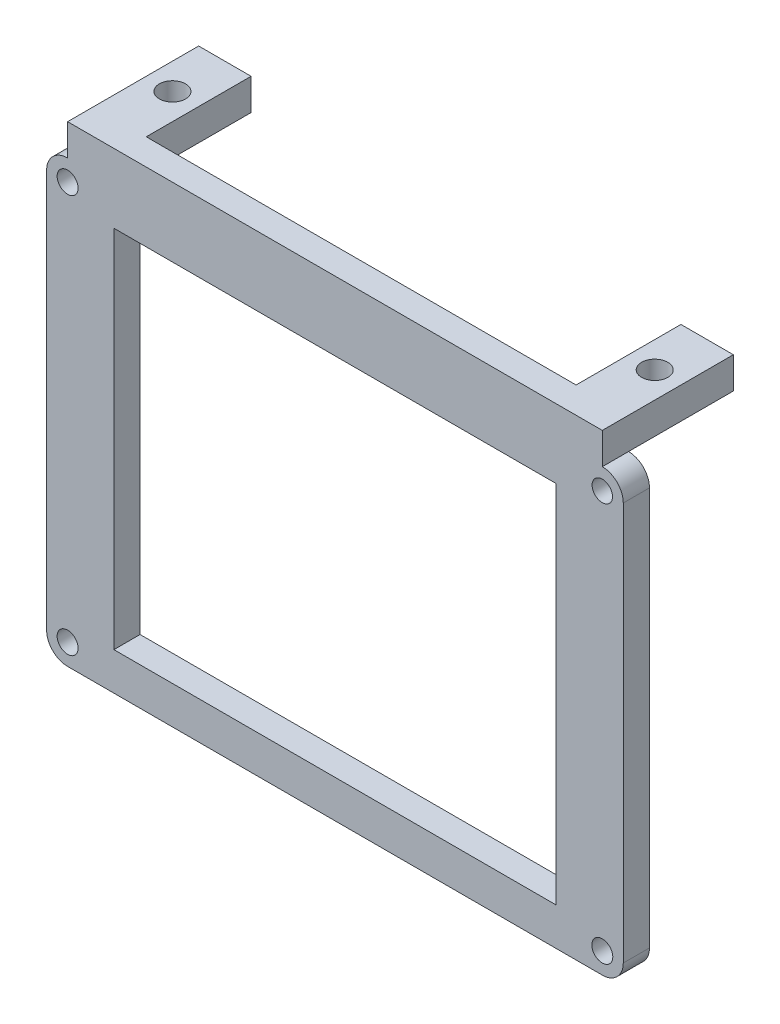
SolidWorks part; units mm, degrees
ref_plane "前视基准面" through (0, 0, 0) normal (0, 0, 1) x (1, 0, 0)
ref_plane "上视基准面" through (0, 0, 0) normal (0, 1, 0) x (1, 0, 0)
ref_plane "右视基准面" through (0, 0, 0) normal (1, 0, 0) x (0, 0, -1)
sketch "草图1" plane through (0, 0, 0) normal (0, 0, 1) x (1, 0, 0)
  line L0 (-38.0886, 27.2715) -> (71.9114, -56.7285) construction
  line L1 (-34.0886, 27.2715) -> (67.9114, 27.2715)
  line L2 (-38.0886, 23.2715) -> (-38.0886, -52.7285)
  line L3 (-34.0886, -56.7285) -> (67.9114, -56.7285)
  line L4 (71.9114, 23.2715) -> (71.9114, -52.7285)
  line L10 (-34.0886, 23.2715) -> (67.9114, -52.7285) construction
  line L11 (-34.0886, -52.7285) -> (67.9114, 23.2715) construction
  circle A0 centre (67.9114, 23.2715) radius 1.9459
  circle A1 centre (-34.0886, 23.2715) radius 2
  circle A2 centre (67.9114, -52.7285) radius 2
  circle A3 centre (-34.0886, -52.7285) radius 2
  arc A4 (67.9114, 27.2715) -> (71.9114, 23.2715) centre (67.9114, 23.2715) cw
  arc A5 (-34.0886, 27.2715) -> (-38.0886, 23.2715) centre (-34.0886, 23.2715) ccw
  arc A6 (-38.0886, -52.7285) -> (-34.0886, -56.7285) centre (-34.0886, -52.7285) ccw
  arc A7 (67.9114, -56.7285) -> (71.9114, -52.7285) centre (67.9114, -52.7285) ccw
  point P4 (16.9114, -14.7285)
  point P15 (71.9114, 27.2715)
  point P21 (-38.0886, -56.7285)
  dimension "D5" = 4
  dimension "D6" = 4
  dimension "D7" = 4
  dimension "D8" = 4
  dimension "D1" = 110
  dimension "D2" = 84
  dimension "D3" = 102
  dimension "D4" = 76
extrude "凸台-拉伸1" add sketch "草图1" along normal blind 5
sketch "草图2" plane through (0, 27.2715, 0) normal (0, 1, 0) x (1, 0, 0)
  line L0 (-34.0886, 0) -> (-24.0886, 20) construction
  line L1 (-34.0886, -5) -> (-24.0886, -5)
  line L2 (-34.0886, -5) -> (-34.0886, 20)
  line L3 (-34.0886, 20) -> (-24.0886, 20)
  line L4 (-24.0886, -5) -> (-24.0886, 20)
  line L5 (67.9114, -5) -> (57.9114, -5)
  line L6 (67.9114, -5) -> (67.9114, 20)
  line L7 (67.9114, 20) -> (57.9114, 20)
  line L8 (57.9114, -5) -> (57.9114, 20)
  line L9 (67.9114, 0) -> (57.9114, 20) construction
  line L10 (67.9114, 0) -> (-34.0886, 0) construction
  line L11 (-24.0886, -5) -> (57.9114, -5)
  line L12 (-24.0886, -5) -> (-24.0886, 0)
  line L13 (-24.0886, 0) -> (57.9114, 0)
  line L14 (57.9114, -5) -> (57.9114, 0)
  circle A0 centre (-29.0886, 10) radius 2.5
  circle A1 centre (62.9114, 10) radius 2.5
  line M10 (67.9114, 0) -> (-34.0886, 0)
  line M11 (-34.0886, 0) -> (-34.0886, -5)
  line M12 (-34.0886, -5) -> (67.9114, -5)
  line M13 (67.9114, -5) -> (67.9114, 0)
  dimension "D1" = 10
  dimension "D2" = 25
  dimension "D3" = 10
  dimension "D4" = 25
extrude "凸台-拉伸2" add sketch "草图2" along normal blind 6 contours L4 L3 L2 A0 M10 | L4 M12 M10 M11 | L8 L4 M12 M10 | L8 L6 L7 A1 M10 | L8 M12 M13 M10
sketch "草图3" plane through (0, 0, 5) normal (0, 0, 1) x (1, 0, 0)
  line L0 (-33.9461, 26.2295) -> (67.9114, -56.7285) construction
  line L1 (67.9114, -56.7285) -> (-34.0886, -56.7285) construction
  line L2 (-34.0886, -56.7285) -> (67.9114, 27.2715) construction
  line L4 (-25.2619, 20.0825) -> (59.0846, 20.0825)
  line L5 (-25.2619, 20.0825) -> (-25.2619, -49.5396)
  line L6 (-25.2619, -49.5396) -> (59.0846, -49.5396)
  line L7 (59.0846, 20.0825) -> (59.0846, -49.5396)
  line L8 (-25.2619, 20.0825) -> (59.0846, -49.5396) construction
  line L9 (-25.2619, -49.5396) -> (59.0846, 20.0825) construction
  point P3 (16.9114, -14.7285)
extrude "切除-拉伸1" cut sketch "草图3" against normal blind 6
